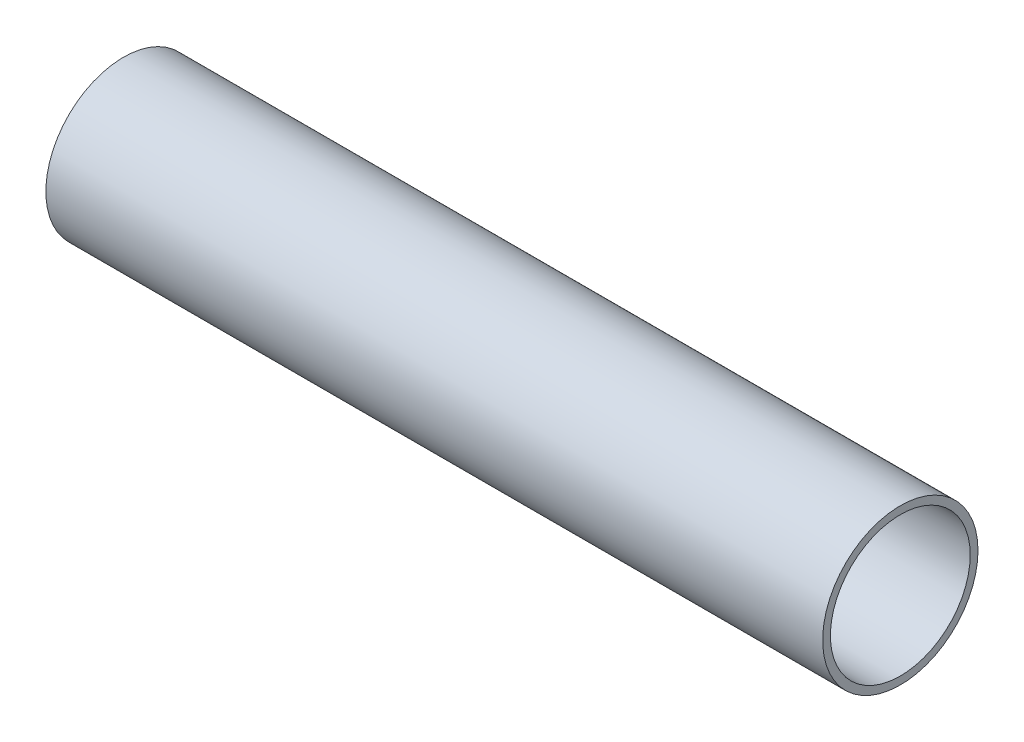
SolidWorks part; units mm, degrees
ref_plane "前视基准面" through (0, 0, 0) normal (0, 0, 1) x (1, 0, 0)
ref_plane "上视基准面" through (0, 0, 0) normal (0, 1, 0) x (1, 0, 0)
ref_plane "右视基准面" through (0, 0, 0) normal (1, 0, 0) x (0, 0, -1)
other "Configuration Table"
sketch "草图1" plane through (0, 0, 0) normal (1, 0, 0) x (0, 0, -1)
  circle A0 centre (0, 0) radius 20
  circle A1 centre (0, 0) radius 18
  dimension "D1" = 36
  dimension "D2" = 40
extrude "凸台-拉伸1" add sketch "草图1" along normal blind 200
